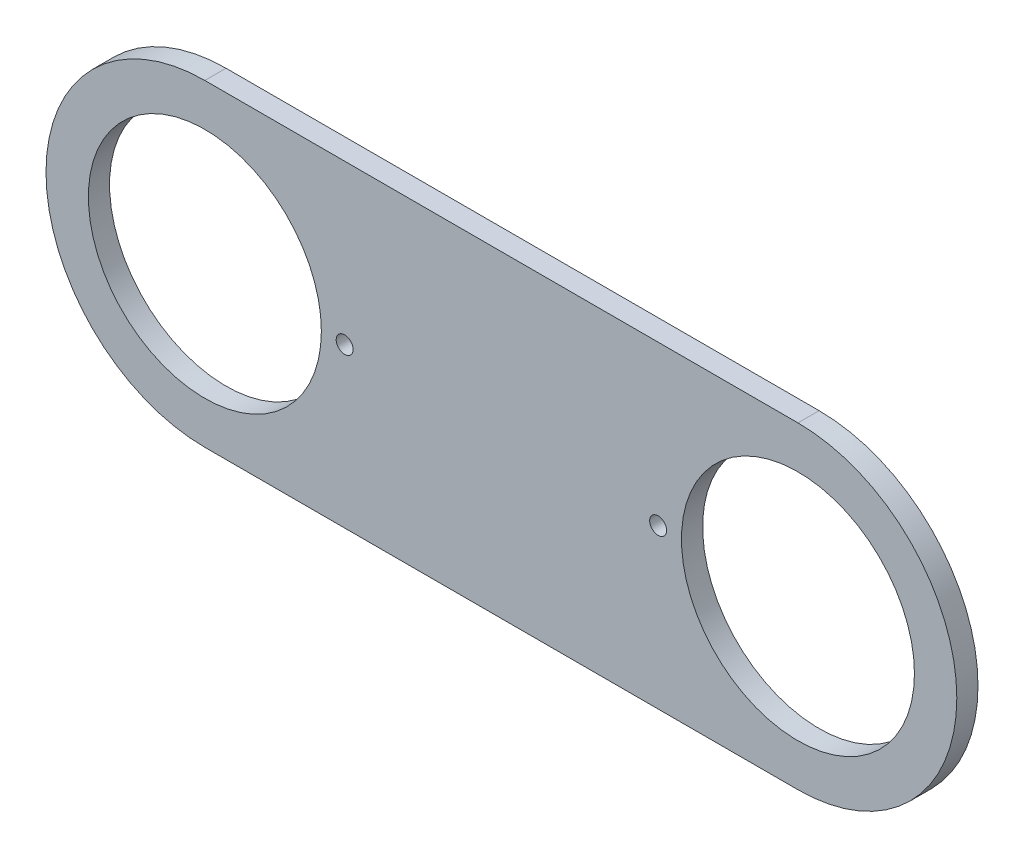
SolidWorks part; units mm, degrees
ref_plane "前视基准面" through (0, 0, 0) normal (0, 0, 1) x (1, 0, 0)
ref_plane "上视基准面" through (0, 0, 0) normal (0, 1, 0) x (1, 0, 0)
ref_plane "右视基准面" through (0, 0, 0) normal (1, 0, 0) x (0, 0, -1)
other "Configuration Table"
sketch "草图1" plane through (0, 0, 0) normal (0, 0, 1) x (1, 0, 0)
  line L0 (0, 0) -> (140, 0) construction
  line L1 (0, 37.5) -> (140, 37.5)
  line L2 (0, -37.5) -> (140, -37.5)
  arc A0 (0, 37.5) -> (0, -37.5) centre (0, 0) ccw
  arc A1 (140, -37.5) -> (140, 37.5) centre (140, 0) ccw
  circle A2 centre (0, 0) radius 27.5
  circle A3 centre (140, 0) radius 27.5
  circle A4 centre (0, 0) radius 33 construction
  circle A5 centre (140, 0) radius 33 construction
  circle A6 centre (33, 0) radius 2
  circle A7 centre (107, 0) radius 2
  dimension "D1" = 75
  dimension "D2" = 75
  dimension "D4" = 55
  dimension "D5" = 55
  dimension "D6" = 66
  dimension "D7" = 4
  dimension "D8" = 66
  dimension "D9" = 4
  dimension "D3" = 140
extrude "凸台-拉伸1" add sketch "草图1" along normal blind 5
